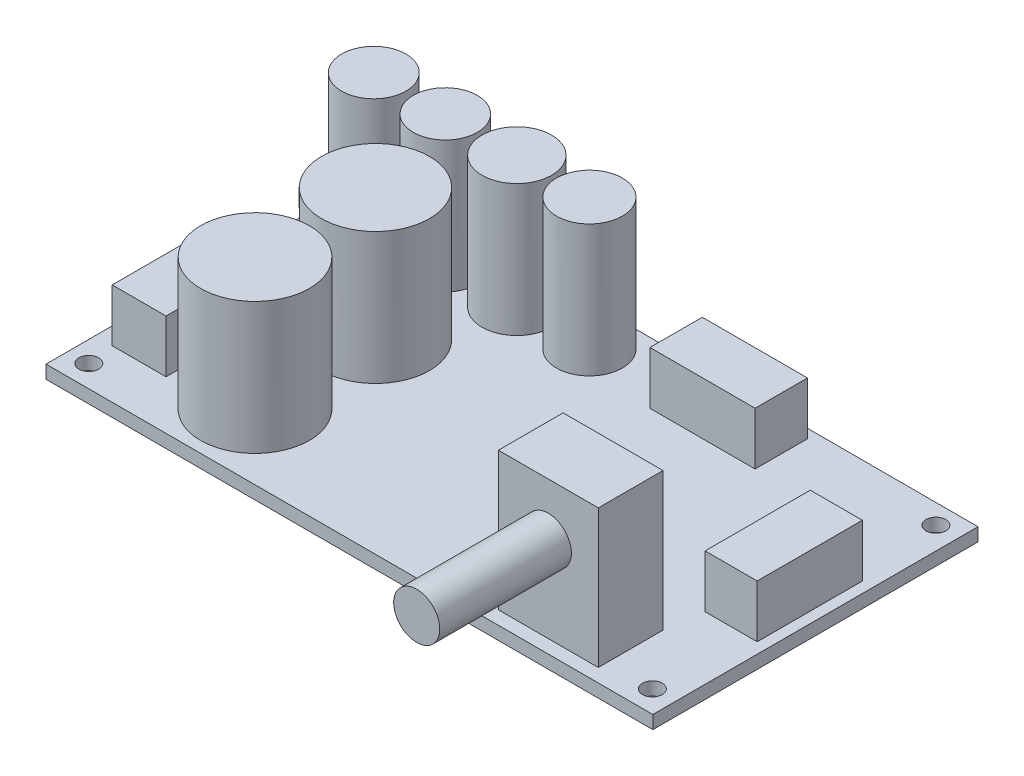
SolidWorks part; units mm, degrees
ref_plane "Front Plane" through (0, 0, 0) normal (0, 0, 1) x (1, 0, 0)
ref_plane "Top Plane" through (0, 0, 0) normal (0, 1, 0) x (1, 0, 0)
ref_plane "Right Plane" through (0, 0, 0) normal (1, 0, 0) x (0, 0, -1)
sketch "Sketch1" plane through (0, 0, 0) normal (0, 1, 0) x (1, 0, 0)
  line L0 (179.6854, 291.801) -> (898.4268, 291.801) construction
  line L2 (0, 0) -> (92.2, 0)
  line L3 (0, 0) -> (0, 49.4)
  line L4 (0, 49.4) -> (92.2, 49.4)
  line L5 (92.2, 0) -> (92.2, 49.4)
  line L6 (2.6114, 23.6201) -> (10.7895, 23.6201)
  line L7 (2.6114, 23.6201) -> (2.6114, 7.4469)
  line L8 (2.6114, 7.4469) -> (10.7895, 7.4469)
  line L9 (10.7895, 23.6201) -> (10.7895, 7.4469)
  line L10 (51.6901, 48.0224) -> (67.6705, 48.0224)
  line L11 (51.6901, 48.0224) -> (51.6901, 40.063)
  line L12 (51.6901, 40.063) -> (67.6705, 40.063)
  line L13 (67.6705, 48.0224) -> (67.6705, 40.063)
  line L14 (82.6478, 33.4703) -> (90.5595, 33.4703)
  line L15 (82.6478, 33.4703) -> (82.6478, 17.4908)
  line L16 (82.6478, 17.4908) -> (90.5595, 17.4908)
  line L17 (90.5595, 33.4703) -> (90.5595, 17.4908)
  line L18 (66.6969, 11.8685) -> (81.8745, 11.8685)
  line L19 (66.6969, 11.8685) -> (66.6969, 2.0385)
  line L20 (66.6969, 2.0385) -> (81.8745, 2.0385)
  line L21 (81.8745, 11.8685) -> (81.8745, 2.0385)
  circle A0 centre (3.174, 3.3317) radius 1.5
  circle A1 centre (88.7994, 46.406) radius 1.5
  circle A2 centre (88.7994, 3.3317) radius 1.5
  circle A3 centre (21.7942, 9.9605) radius 8.2622
  circle A4 centre (21.7942, 28.2648) radius 8.1929
  circle A5 centre (6.542, 43.2597) radius 4.8866
  circle A6 centre (17.4088, 43.2597) radius 4.8664
  circle A7 centre (28.2757, 43.2597) radius 5.2896
  circle A8 centre (39.3032, 43.2597) radius 5.0063
  dimension "D3" = 3
  dimension "D4" = 3
  dimension "D5" = 3
  dimension "D1" = 92.2
  dimension "D2" = 49.4
  dimension "D6" = 3.174
extrude "Boss-Extrude1" add sketch "Sketch1" along normal blind 2
sketch "Sketch3" plane through (0, 0, 0) normal (0, -1, 0) x (-1, 0, 0)
  line L1 (-2.6114, 7.4469) -> (-10.7895, 7.4469)
  line L2 (-2.6114, 7.4469) -> (-2.6114, 23.6201)
  line L3 (-2.6114, 23.6201) -> (-10.7895, 23.6201)
  line L4 (-10.7895, 7.4469) -> (-10.7895, 23.6201)
  line L5 (-51.6901, 40.063) -> (-67.6705, 40.063)
  line L6 (-51.6901, 40.063) -> (-51.6901, 48.0224)
  line L7 (-51.6901, 48.0224) -> (-67.6705, 48.0224)
  line L8 (-67.6705, 40.063) -> (-67.6705, 48.0224)
  line L9 (-82.6478, 17.4908) -> (-90.5595, 17.4908)
  line L10 (-82.6478, 17.4908) -> (-82.6478, 33.4703)
  line L11 (-82.6478, 33.4703) -> (-90.5595, 33.4703)
  line L12 (-90.5595, 17.4908) -> (-90.5595, 33.4703)
extrude "Boss-Extrude2" add sketch "Sketch3" against normal blind 10
sketch "Sketch4" plane through (0, 0, 0) normal (0, -1, 0) x (-1, 0, 0)
  circle A0 centre (-21.7942, 28.2648) radius 8.1929
  circle A1 centre (-21.7942, 9.9605) radius 8.2622
  circle A2 centre (-6.542, 43.2597) radius 4.8866
  circle A3 centre (-17.4088, 43.2597) radius 4.8664
  circle A4 centre (-28.2757, 43.2597) radius 5.2896
  circle A5 centre (-39.3032, 43.2597) radius 5.0063
extrude "Boss-Extrude3" add sketch "Sketch4" against normal blind 22
sketch "Sketch5" plane through (0, 0, 0) normal (0, -1, 0) x (-1, 0, 0)
  line L1 (-66.6969, 2.0385) -> (-81.8745, 2.0385)
  line L2 (-66.6969, 2.0385) -> (-66.6969, 11.8685)
  line L3 (-66.6969, 11.8685) -> (-81.8745, 11.8685)
  line L4 (-81.8745, 2.0385) -> (-81.8745, 11.8685)
extrude "Boss-Extrude4" add sketch "Sketch5" against normal blind 23
sketch "Sketch6" plane through (0, 0, -2.0385) normal (0, 0, 1) x (1, 0, 0)
  line L2 (0, 2) -> (92.2, 2) construction
  circle A0 centre (74.2857, 15) radius 3.5
  dimension "D1" = 7
  dimension "D2" = 13
extrude "Boss-Extrude5" add sketch "Sketch6" along normal blind 20
